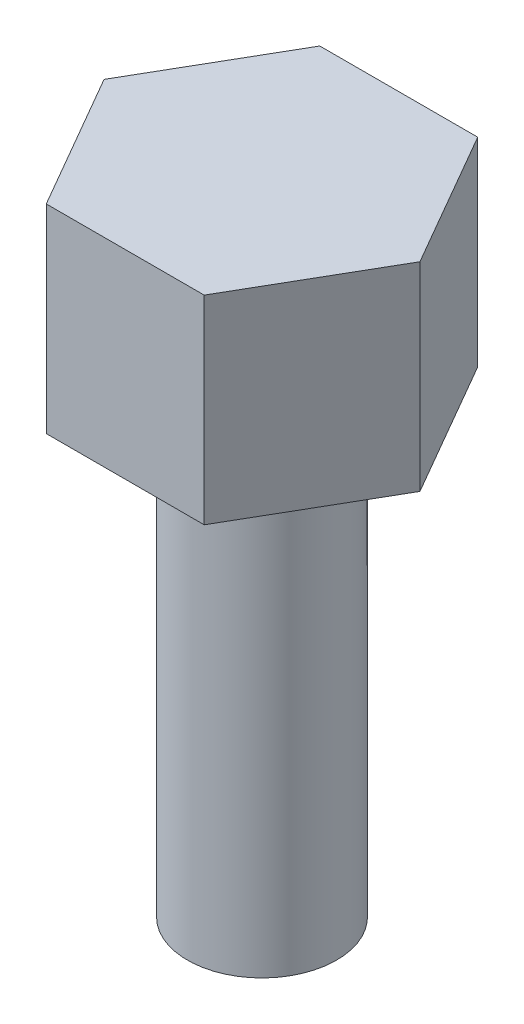
SolidWorks part; units mm, degrees
ref_plane "Front Plane" through (0, 0, 0) normal (0, 0, 1) x (1, 0, 0)
ref_plane "Top Plane" through (0, 0, 0) normal (0, 1, 0) x (1, 0, 0)
ref_plane "Right Plane" through (0, 0, 0) normal (1, 0, 0) x (0, 0, -1)
sketch "Sketch1" plane through (0, 0, 0) normal (0, 1, 0) x (1, 0, 0)
  line L1 (3.1754, 0) -> (1.5877, 2.75)
  line L2 (1.5877, 2.75) -> (-1.5877, 2.75)
  line L3 (-1.5877, 2.75) -> (-3.1754, 0)
  line L4 (-3.1754, 0) -> (-1.5877, -2.75)
  line L5 (-1.5877, -2.75) -> (1.5877, -2.75)
  line L6 (1.5877, -2.75) -> (3.1754, 0)
  circle A0 centre (0, 0) radius 2.75 construction
  circle A1 centre (0, 0) radius 1.5
  dimension "D1" = 3
  dimension "D2" = 5.5
extrude "Boss-Extrude1" add sketch "Sketch1" along normal blind 4 contours L3 L4 L5 L6 L1 L2
sketch "Sketch2" plane through (0, 0, 0) normal (0, -1, 0) x (1, 0, 0)
  circle A0 centre (0, 0) radius 1.5
  dimension "D1" = 3
extrude "Boss-Extrude2" add sketch "Sketch2" along normal blind 9
